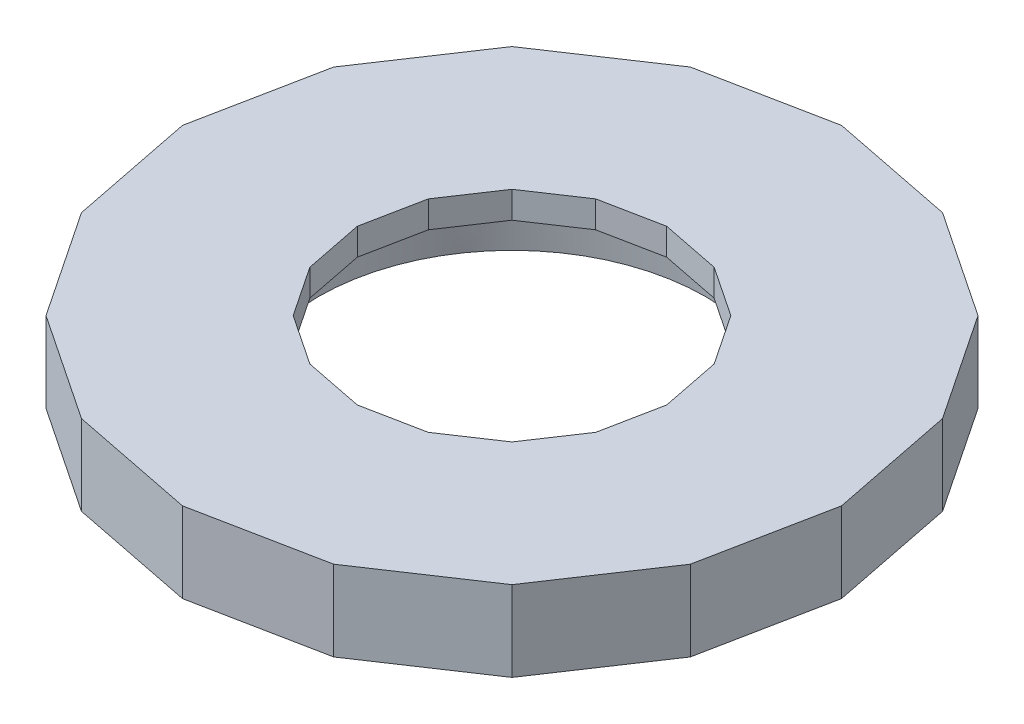
SolidWorks part; units mm, degrees
ref_plane "Front Plane" through (0, 0, 0) normal (0, 0, 1) x (1, 0, 0)
ref_plane "Top Plane" through (0, 0, 0) normal (0, 1, 0) x (1, 0, 0)
ref_plane "Right Plane" through (0, 0, 0) normal (1, 0, 0) x (0, 0, -1)
sketch "Sketch1" plane through (0, 0, 0) normal (0, 1, 0) x (1, 0, 0)
  line L0 (-78.1177, 0) -> (0, 0) construction
  line L1 (-78.1177, 0) -> (-72.1713, -29.8943)
  line L2 (-72.1713, -29.8943) -> (-55.2375, -55.2375)
  line L3 (-55.2375, -55.2375) -> (-29.8943, -72.1713)
  line L4 (-29.8943, -72.1713) -> (0, -78.1177)
  line L5 (0, -78.1177) -> (29.8943, -72.1713)
  line L6 (29.8943, -72.1713) -> (55.2375, -55.2375)
  line L7 (55.2375, -55.2375) -> (72.1713, -29.8943)
  line L8 (72.1713, -29.8943) -> (78.1177, 0)
  line L9 (78.1177, 0) -> (72.1713, 29.8943)
  line L10 (72.1713, 29.8943) -> (55.2375, 55.2375)
  line L11 (55.2375, 55.2375) -> (29.8943, 72.1713)
  line L12 (29.8943, 72.1713) -> (0, 78.1177)
  line L13 (0, 78.1177) -> (-29.8943, 72.1713)
  line L14 (-29.8943, 72.1713) -> (-55.2375, 55.2375)
  line L15 (-55.2375, 55.2375) -> (-72.1713, 29.8943)
  line L16 (-72.1713, 29.8943) -> (-78.1177, 0)
  line L18 (-36.6815, 0) -> (-33.8893, -14.0374)
  line L19 (-33.8893, -14.0374) -> (-25.9377, -25.9377)
  line L20 (-25.9377, -25.9377) -> (-14.0374, -33.8893)
  line L21 (-14.0374, -33.8893) -> (0, -36.6815)
  line L22 (0, -36.6815) -> (14.0374, -33.8893)
  line L23 (14.0374, -33.8893) -> (25.9377, -25.9377)
  line L24 (25.9377, -25.9377) -> (33.8893, -14.0374)
  line L25 (33.8893, -14.0374) -> (36.6815, 0)
  line L26 (36.6815, 0) -> (33.8893, 14.0374)
  line L27 (33.8893, 14.0374) -> (25.9377, 25.9377)
  line L28 (25.9377, 25.9377) -> (14.0374, 33.8893)
  line L29 (14.0374, 33.8893) -> (0, 36.6815)
  line L30 (0, 36.6815) -> (-14.0374, 33.8893)
  line L31 (-14.0374, 33.8893) -> (-25.9377, 25.9377)
  line L32 (-25.9377, 25.9377) -> (-33.8893, 14.0374)
  line L33 (-33.8893, 14.0374) -> (-36.6815, 0)
  circle A0 centre (0, 0) radius 76.6167 construction
  circle A1 centre (0, 0) radius 35.9767 construction
  dimension "D1" = 30.48
  dimension "D2" = 40.64
extrude "Boss-Extrude1" add sketch "Sketch1" along normal blind 19.05
sketch "Sketch5" plane through (0, 19.05, 0) normal (0, 1, 0) x (1, 0, 0)
  circle A0 centre (0, 0) radius 76.2
  dimension "D1" = 152.4
sketch "Sketch6" plane through (0, 0, 0) normal (0, 0, 1) x (1, 0, 0)
  line L0 (-44.7832, 12.7) -> (-45.8943, 0)
  line L1 (-55.2375, 0) -> (-29.8943, 0) construction
  line L2 (-45.8943, 0) -> (-10.2189, 0)
  line L3 (-29.8943, 0) -> (0, 0) construction
  line L4 (-10.2189, 0) -> (-10.2189, 12.7)
  line L5 (76.2, 19.05) -> (-76.2, 19.05) construction
  line L6 (-44.7832, 12.7) -> (-10.2189, 12.7)
  line L7 (0, 0) -> (0, 19.05) construction
  dimension "D1" = 85
  dimension "D2" = 12.7
revolve "Cut-Revolve1" cut sketch "Sketch6" angle 360 about L7
